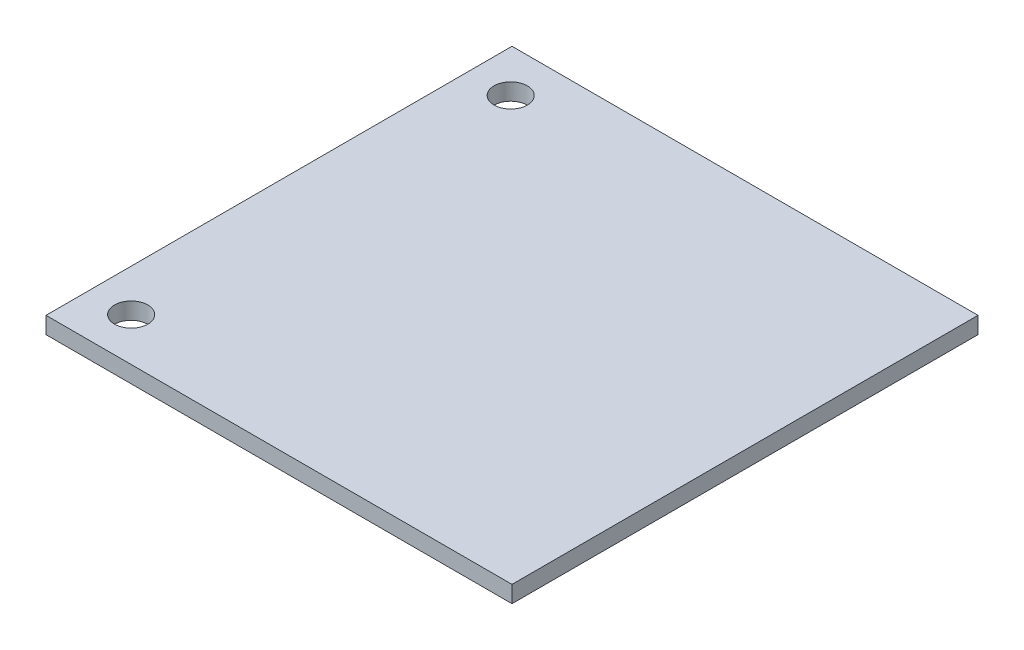
SolidWorks part; units mm, degrees
ref_plane "Front Plane" through (0, 0, 0) normal (0, 0, 1) x (1, 0, 0)
ref_plane "Top Plane" through (0, 0, 0) normal (0, 1, 0) x (1, 0, 0)
ref_plane "Right Plane" through (0, 0, 0) normal (1, 0, 0) x (0, 0, -1)
sketch "Sketch1" plane through (0, 0, 0) normal (0, 1, 0) x (1, 0, 0)
  line L1 (-22.225, 22.225) -> (22.225, 22.225)
  line L2 (-22.225, 22.225) -> (-22.225, -22.225)
  line L3 (-22.225, -22.225) -> (22.225, -22.225)
  line L4 (22.225, 22.225) -> (22.225, -22.225)
  circle A0 centre (-18.225, 18.1) radius 1.59
  circle A1 centre (-18.225, -18.1) radius 1.59
  dimension "D4" = 18.1
  dimension "D6" = 3.18
  dimension "D7" = 4
  dimension "D8" = 4
  dimension "D1" = 22.225
  dimension "D2" = 22.225
  dimension "D3" = 44.45
  dimension "D5" = 18.1
extrude "Boss-Extrude1" add sketch "Sketch1" along normal blind 1.6
